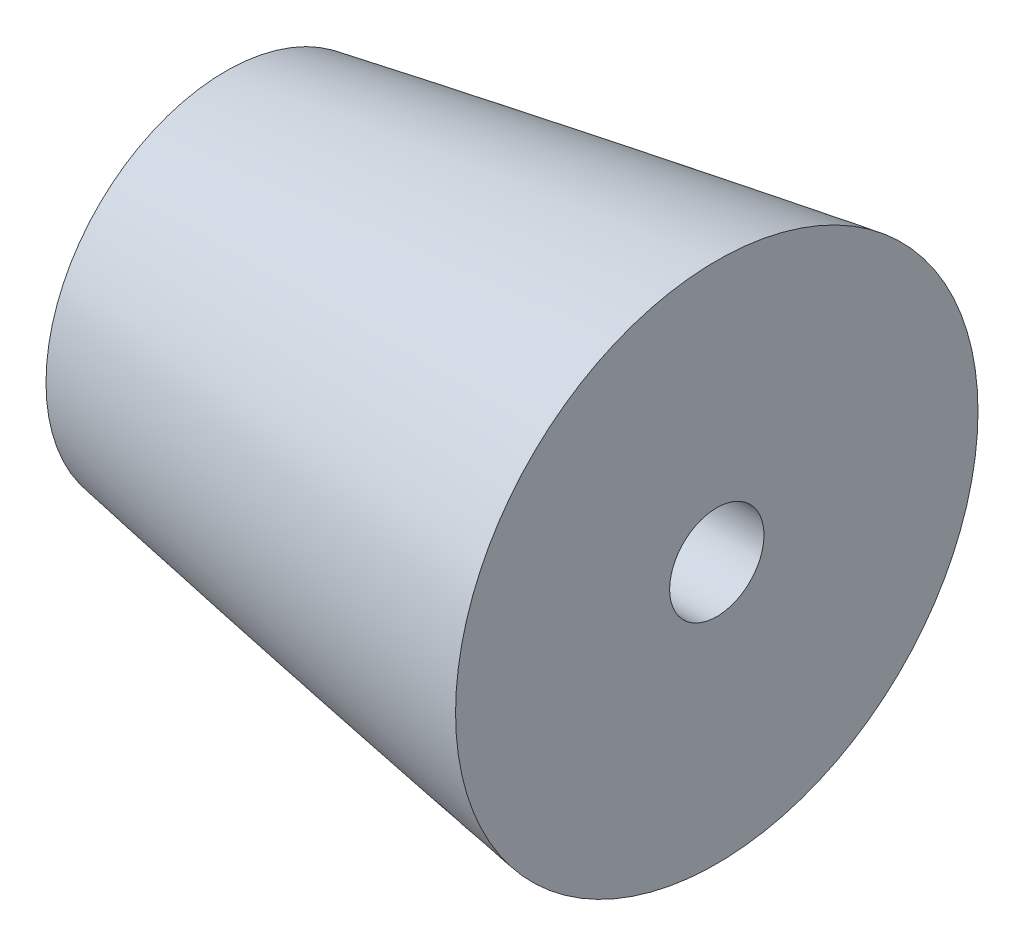
SolidWorks part; units mm, degrees
ref_plane "Front Plane" through (0, 0, 0) normal (0, 0, 1) x (1, 0, 0)
ref_plane "Top Plane" through (0, 0, 0) normal (0, 1, 0) x (1, 0, 0)
ref_plane "Right Plane" through (0, 0, 0) normal (1, 0, 0) x (0, 0, -1)
sketch "Sketch2" plane through (0, 0, 0) normal (0, 0, 1) x (1, 0, 0)
  line L7 (70.2313, 3.5582) -> (95.5917, 3.5582)
  line L9 (70.2313, 0.5281) -> (95.5917, 0.5281) construction
  line L10 (70.2313, 3.5582) -> (70.2313, 8.7831)
  line L12 (70.2313, 8.7831) -> (64.0515, 8.7831)
  line L15 (64.0515, 8.7831) -> (64.0515, 12.0756)
  line L16 (95.5917, 3.5582) -> (95.5917, 17.3072)
  spline S0 degree 4 poles (60.3452, 14.6419) (60.4128, 14.654) (60.5324, 14.6753) (60.6359, 14.694) (61.2064, 14.7955) (61.6222, 14.8702) (63.1101, 15.1336) (63.6694, 15.2324) (65.2662, 15.513) (66.1537, 15.6677) (67.3673, 15.8791) (68.3864, 16.0552) (69.5229, 16.2512) (70.5891, 16.434) (71.697, 16.6233) (72.7818, 16.8076) (73.8776, 16.9932) (74.9722, 17.1777) (76.0688, 17.3619) (77.457, 17.5938) (79.0806, 17.864) (81.0519, 18.189) (83.1652, 18.5358) (85.4672, 18.9093) (87.4738, 19.2339) (89.9602, 19.6311) (91.6588, 19.9023) (94.4531, 20.3426) (95.4727, 20.5025) (96.8706, 20.7209) (97.8271, 20.87) (98.0554, 20.9052) (98.3528, 20.9516) (98.4279, 20.9632) knots 0 0 0 0 0 0.005202 0.010404 0.020808 0.041616 0.082728 0.111453 0.140178 0.168903 0.197628 0.226353 0.255078 0.283803 0.312528 0.341253 0.369978 0.398703 0.427428 0.45713 0.51458 0.57203 0.62948 0.68693 0.74438 0.80183 0.85928 0.91673 0.958365 0.979182 0.989591 1 1 1 1 1 construction
  spline S1 degree 4 poles (63.5, 15.2023) (63.7276, 15.2425) (64.1851, 15.323) (65.2662, 15.513) (66.1537, 15.6677) (67.3673, 15.8791) (68.3864, 16.0552) (69.5229, 16.2512) (70.5891, 16.434) (71.697, 16.6233) (72.7818, 16.8076) (73.8776, 16.9932) (74.9722, 17.1777) (76.0688, 17.3619) (77.457, 17.5938) (79.0806, 17.864) (81.0519, 18.189) (83.1652, 18.5358) (85.4672, 18.9093) (87.4738, 19.2339) (89.9602, 19.6311) (91.6588, 19.9023) (93.9094, 20.2569) (94.7933, 20.3958) (95.25, 20.4674) knots 0.082728 0.082728 0.082728 0.082728 0.082728 0.111453 0.140178 0.168903 0.197628 0.226353 0.255078 0.283803 0.312528 0.341253 0.369978 0.398703 0.427428 0.45713 0.51458 0.57203 0.62948 0.68693 0.74438 0.80183 0.85928 0.91673 0.91673 0.91673 0.91673 0.91673 construction
  spline S2 degree 1 poles (64.0515, 12.0756) (95.7417, 17.3308) knots 0 0 1 1 construction
  spline S3 degree 3 poles (64.0515, 12.0756) (64.1956, 12.101) (64.464, 12.1483) (64.985, 12.2399) (65.551, 12.3393) (66.0618, 12.4287) (66.5181, 12.5083) (67.1553, 12.6194) (68.0319, 12.7718) (68.9787, 12.9355) (70.3255, 13.1677) (72.6114, 13.5591) (75.9257, 14.12) (79.2102, 14.6675) (81.8732, 15.1064) (83.8214, 15.4255) (85.8645, 15.7573) (87.4335, 16.011) (88.8037, 16.2309) (89.843, 16.3971) (90.7934, 16.5489) (91.6939, 16.6923) (92.7201, 16.8549) (93.877, 17.0375) (94.845, 17.1899) (95.3657, 17.2718) (95.6419, 17.3151) (95.7027, 17.3246) (95.7417, 17.3308) knots 0.082728 0.082728 0.082728 0.082728 0.095759 0.10879 0.121822 0.134853 0.147884 0.160916 0.186978 0.213041 0.239103 0.291228 0.395479 0.499729 0.551854 0.603979 0.656104 0.708229 0.734292 0.760354 0.786417 0.812479 0.838542 0.864605 0.890667 0.910808 0.913177 0.91673 0.91673 0.91673 0.91673 only from (64.0515, 12.0756) to (95.5917, 17.3072)
  dimension "D1" = 3.175
  dimension "D2" = 8.255
  dimension "D3" = 25.3604
revolve "Revolve1" add sketch "Sketch2" angle 360 about L9
